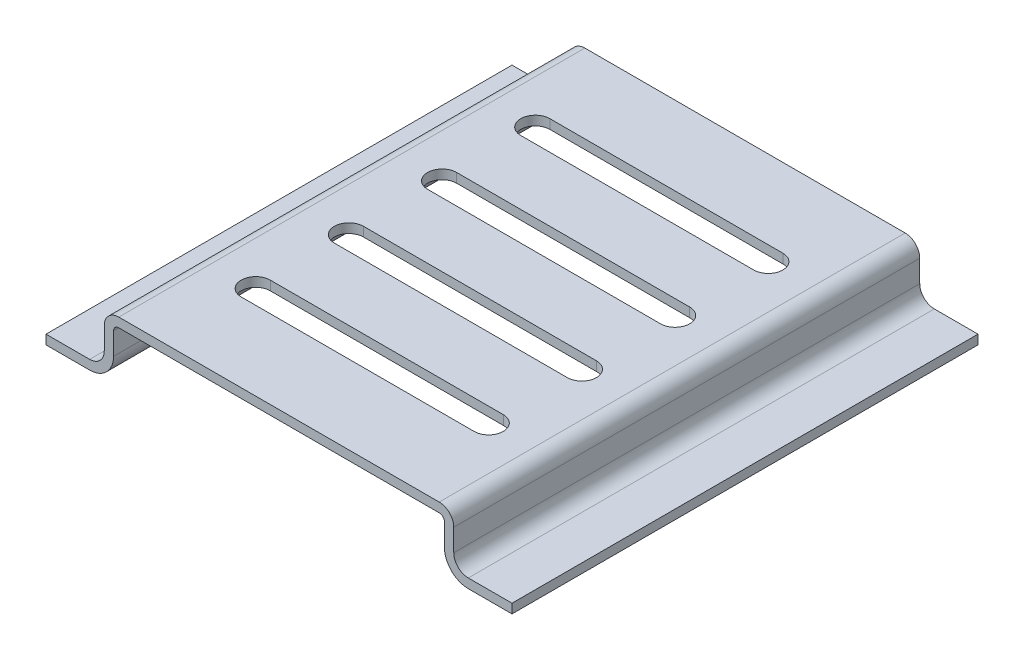
SolidWorks part; units mm, degrees
ref_plane "Front Plane" through (0, 0, 0) normal (0, 0, 1) x (1, 0, 0)
ref_plane "Top Plane" through (0, 0, 0) normal (0, 1, 0) x (1, 0, 0)
ref_plane "Right Plane" through (0, 0, 0) normal (1, 0, 0) x (0, 0, -1)
sketch "Sketch1" plane through (0, 0, 0) normal (0, 0, 1) x (1, 0, 0)
  line L0 (0, 0) -> (9.525, 0)
  line L1 (12.7, 3.175) -> (12.7, 7.9847)
  line L2 (15.875, 11.1597) -> (85.725, 11.1597)
  line L3 (88.9, 7.9847) -> (88.9, 3.175)
  line L4 (92.075, 0) -> (101.6, 0)
  arc A0 (9.525, 0) -> (12.7, 3.175) centre (9.525, 3.175) ccw
  arc A1 (88.9, 3.175) -> (92.075, 0) centre (92.075, 3.175) ccw
  arc A2 (85.725, 11.1597) -> (88.9, 7.9847) centre (85.725, 7.9847) cw
  arc A3 (12.7, 7.9847) -> (15.875, 11.1597) centre (15.875, 7.9847) cw
  point P9 (12.7, 0)
  point P12 (88.9, 0)
  point P15 (88.9, 11.1597)
  point P18 (12.7, 11.1597)
  dimension "D4" = 3.175
  dimension "D1" = 76.2
  dimension "D2" = 12.7
  dimension "D3" = 12.7
extrude "Extrude-Thin1" add sketch "Sketch1" against normal blind 101.6 thin
sketch "Sketch2" plane through (0, 0, 0) normal (0, 1, 0) x (1, 0, 0)
  line L0 (50.8, 0) -> (50.8, 20.32) construction
  line L1 (15.875, 0) -> (85.725, 0) construction
  line L2 (25.4, 20.32) -> (76.2, 20.32) construction
  line L3 (25.4, 23.495) -> (76.2, 23.495)
  line L4 (25.4, 17.145) -> (76.2, 17.145)
  arc A0 (25.4, 23.495) -> (25.4, 17.145) centre (25.4, 20.32) ccw
  arc A1 (76.2, 17.145) -> (76.2, 23.495) centre (76.2, 20.32) ccw
  point P6 (50.8, 20.32)
  dimension "D1" = 6.35
  dimension "D2" = 50.8
  dimension "D3" = 20.32
extrude "Cut-Extrude1" cut sketch "Sketch2" against normal mid plane 99.568
pattern_linear "LPattern1" count 4 spacing 20.32 along (0, 0, -1) of "Cut-Extrude1"
